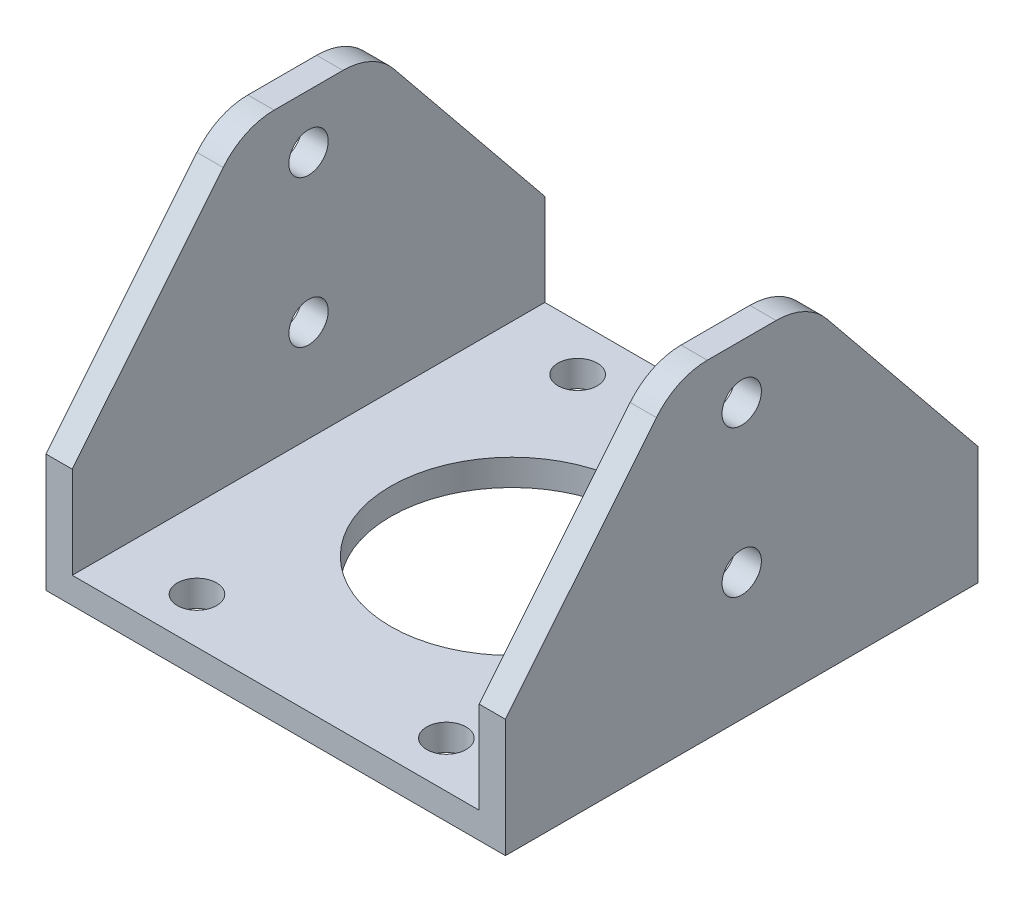
SolidWorks part; units mm, degrees
material "6061 合金"
ref_plane "前视基准面" through (0, 0, 0) normal (0, 0, 1) x (1, 0, 0)
ref_plane "上视基准面" through (0, 0, 0) normal (0, 1, 0) x (1, 0, 0)
ref_plane "右视基准面" through (0, 0, 0) normal (1, 0, 0) x (0, 0, -1)
sketch "草图1" plane through (0, 0, 0) normal (0, 0, 1) x (1, 0, 0)
  line L0 (0, 0) -> (0, 25)
  line L1 (0, 25) -> (2, 25)
  line L2 (2, 25) -> (2, 2)
  line L3 (2, 2) -> (33, 2)
  line L4 (33, 2) -> (33, 25)
  line L5 (33, 25) -> (35, 25)
  line L6 (35, 25) -> (35, 0)
  line L7 (35, 0) -> (0, 0)
  dimension "D2" = 2
  dimension "D1" = 25
  dimension "D3" = 23
  dimension "D4" = 35
  dimension "D6" = 2
extrude "凸台-拉伸1" add sketch "草图1" along normal blind 36
sketch "草图2" plane through (0, 0, 0) normal (0, -1, 0) x (1, 0, 0)
  line L0 (0, 18) -> (35, 18) construction
  line L1 (0, 36) -> (0, 0) construction
  line L2 (35, 36) -> (35, 0) construction
  line L3 (17.5, 36) -> (17.5, 0) construction
  line L4 (0, 36) -> (35, 36) construction
  line L5 (0, 0) -> (35, 0) construction
  circle A0 centre (17.5, 18) radius 9.25
  dimension "D1" = 18.5
extrude "切除-拉伸1" cut sketch "草图2" against normal blind 12
sketch "草图3" plane through (0, 0, 0) normal (-1, 0, 0) x (0, 0, 1)
  line L0 (18, 25) -> (18, 0) construction
  line L3 (36, 25) -> (0, 25) construction
  line L4 (36, 0) -> (0, 0) construction
  line L5 (0, 12.5) -> (36, 12.5) construction
  line L6 (0, 25) -> (0, 0) construction
  line L7 (36, 25) -> (36, 0) construction
  line L8 (0, 15.3) -> (36, 15.3) construction
  circle A0 centre (18, 20.9) radius 1.5
  circle A1 centre (18, 9.7) radius 1.5
  dimension "D1" = 3
  dimension "D2" = 3
  dimension "D3" = 11.2
  dimension "D4" = 2.8
  dimension "D5" = 5.6
extrude "切除-拉伸2" cut sketch "草图3" against normal blind 54
sketch "草图5" plane through (0, 2, 0) normal (0, 1, 0) x (1, 0, 0)
  line L5 (8, -3.5) -> (27, -3.5) construction
  line L6 (8, -3.5) -> (8, -32.5) construction
  line L7 (8, -32.5) -> (27, -32.5) construction
  line L12 (27, -3.5) -> (27, -32.5) construction
  line L13 (8, -3.5) -> (27, -32.5) construction
  line L14 (8, -32.5) -> (27, -3.5) construction
  circle A4 centre (8, -3.5) radius 1.5
  circle A5 centre (27, -3.5) radius 1.5
  circle A6 centre (8, -32.5) radius 1.5
  circle A7 centre (27, -32.5) radius 1.5
  point P0 (17.5, -18)
  dimension "D3" = 3
  dimension "D4" = 3
  dimension "D5" = 3
  dimension "D6" = 3
  dimension "D1" = 29
  dimension "D2" = 19
extrude "切除-拉伸4" cut sketch "草图5" against normal blind 10
sketch "草图6" plane through (0, 0, 0) normal (-1, 0, 0) x (0, 0, 1)
  line L0 (0, 9) -> (13, 25)
  line L1 (0, 25) -> (0, 0) construction
  line L2 (36, 25) -> (0, 25) construction
  line L3 (13, 25) -> (0, 25)
  line L4 (0, 25) -> (0, 9)
  line L5 (18, 25) -> (18, 0) construction
  line L6 (36, 0) -> (0, 0) construction
  line L7 (36, 25) -> (36, 9)
  line L8 (23, 25) -> (36, 25)
  line L9 (36, 9) -> (23, 25)
  dimension "D1" = 16
  dimension "D2" = 13
extrude "切除-拉伸5" cut sketch "草图6" against normal blind 57
fillet "圆角1" radius 5 4 edges at (1, 25, 13) (1, 25, 23) (34, 25, 13) (34, 25, 23)
